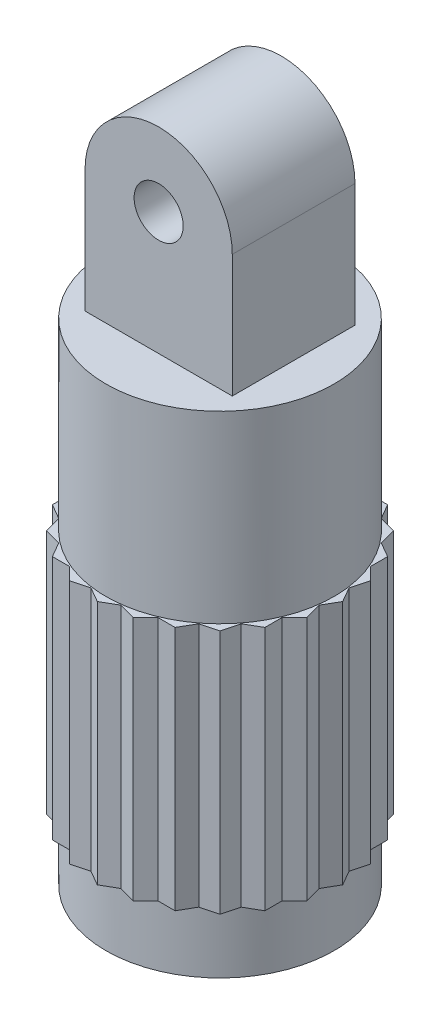
SolidWorks part; units mm, degrees
ref_plane "Front Plane" through (0, 0, 0) normal (0, 0, 1) x (1, 0, 0)
ref_plane "Top Plane" through (0, 0, 0) normal (0, 1, 0) x (1, 0, 0)
ref_plane "Right Plane" through (0, 0, 0) normal (1, 0, 0) x (0, 0, -1)
sketch "Sketch1" plane through (0, 0, 0) normal (0, 0, 1) x (1, 0, 0)
  line L0 (0, 0) -> (0, 112)
  line L1 (-3.9996, 108.0588) -> (-5, 40)
  line L2 (-5, 40) -> (-5, 0)
  line L3 (-5, 0) -> (0, 0)
  arc A0 (0, 112) -> (-3.9996, 108.0588) centre (0, 108) ccw
  dimension "D2" = 4
  dimension "D1" = 112
  dimension "D3" = 5
  dimension "D4" = 40
revolve "Revolve1" [suppressed] add sketch "Sketch1" angle 360 about L0
sketch "Sketch3" plane through (0, 0, 0) normal (0, 1, 0) x (1, 0, 0)
  circle A0 centre (0, 0) radius 4.65
  dimension "D1" = 9.3
extrude "Boss-Extrude1" add sketch "Sketch3" along normal blind 20
sketch "Sketch4" plane through (0, 0, 0) normal (0, 0, 1) x (1, 0, 0)
  line L0 (3, 20) -> (-3, 20)
  line L1 (4.65, 20) -> (-4.65, 20) construction
  line L2 (-3, 20) -> (-3, 25)
  line L3 (-3, 25) -> (3, 25) construction
  line L4 (3, 25) -> (3, 20)
  line L5 (0, 20) -> (0, 25) construction
  arc A0 (3, 25) -> (-3, 25) centre (0, 25) ccw
  circle A1 centre (0, 25) radius 1
  dimension "D2" = 2
  dimension "D1" = 5
  dimension "D3" = 6
extrude "Boss-Extrude2" add sketch "Sketch4" along normal mid plane 5
sketch "Sketch5" plane through (0, 0, 0) normal (0, -1, 0) x (1, 0, 0)
  line L0 (-5, 0) -> (-2.5, -4.3301)
  line L1 (2.5, -4.3301) -> (5, 0)
  line L2 (5, 0) -> (2.5, 4.3301)
  line L3 (2.5, 4.3301) -> (-2.5, 4.3301)
  line L4 (-2.5, 4.3301) -> (-5, 0)
  line L5 (-2.5, -4.3301) -> (2.5, -4.3301)
  circle A0 centre (0, 0) radius 4.3301 construction
  dimension "D1" = 10
extrude "Boss-Extrude3" add sketch "Sketch5" against normal blind 10 from offset 2.5 offset against normal yes
pattern_circular "CirPattern1" count 4 every 15 about axis through (0, 0, 0) along (0, 1, 0) of "Boss-Extrude3"
